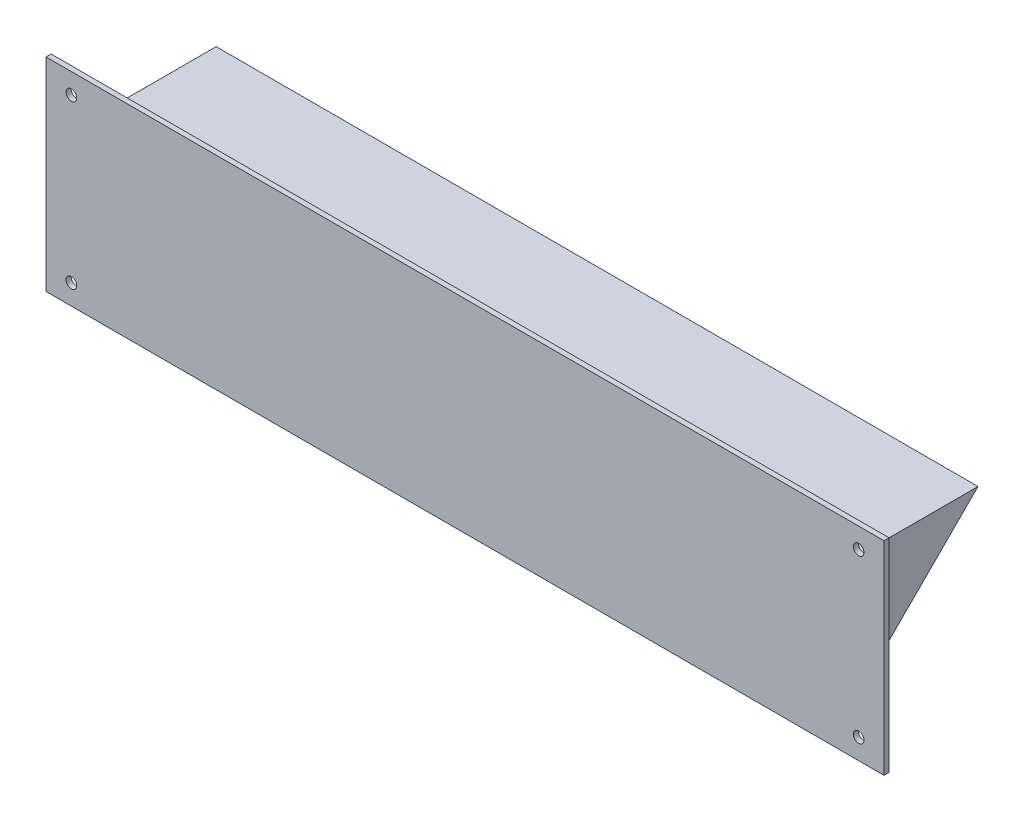
SolidWorks part; units mm, degrees
material "1.4511 (X3CrNb17)"
ref_plane "前视基准面" through (0, 0, 0) normal (0, 0, 1) x (1, 0, 0)
ref_plane "上视基准面" through (0, 0, 0) normal (0, 1, 0) x (1, 0, 0)
ref_plane "右视基准面" through (0, 0, 0) normal (1, 0, 0) x (0, 0, -1)
sketch "草图1" plane through (0, 0, 0) normal (0, 0, 1) x (1, 0, 0)
  line L1 (-165, 40) -> (165, 40)
  line L2 (-165, 40) -> (-165, -40)
  line L3 (-165, -40) -> (165, -40)
  line L4 (165, 40) -> (165, -40)
  line L5 (-165, 40) -> (165, -40) construction
  line L6 (-165, -40) -> (165, 40) construction
  point P0 (0, 0)
  dimension "D1" = 330
  dimension "D2" = 80
extrude "凸台-拉伸1" add sketch "草图1" along normal blind 2
sketch "草图2" plane through (0, 0, 2) normal (0, 0, 1) x (1, 0, 0)
  line L1 (-155, 32) -> (155, 32) construction
  line L2 (-155, 32) -> (-155, -32) construction
  line L3 (-155, -32) -> (155, -32) construction
  line L4 (155, 32) -> (155, -32) construction
  line L5 (-155, 32) -> (155, -32) construction
  line L6 (-155, -32) -> (155, 32) construction
  point P0 (0, 0)
  dimension "D1" = 310
  dimension "D2" = 64
hole_wizard "M5 螺纹孔1" positions "草图3" profile "草图4" tap size "M5" standard "GB" end condition through all
sketch "草图3" plane through (0, 0, 2) normal (0, 0, 1) x (1, 0, 0)
  point P0 (-155, 32)
  point P3 (-155, -32)
  point P6 (155, 32)
  point P9 (155, -32)
sketch "草图4" plane through (-155, 32, 2) normal (1, 0, 0) x (0, -1, 0)
  line L0 (0, 0) -> (0, 2)
  line L1 (0, 2) -> (2.1, 2)
  line L2 (2.1, 2) -> (2.1, 0)
  line L5 (2.1, 0) -> (0, 0)
  line L11 (0, -6.35) -> (0, 107.95) construction
  dimension "通孔螺纹孔钻头直径" = 4.2
  dimension "通孔螺纹孔钻头深度" = 2
cosmetic thread "孔螺蚊线1"
cosmetic thread "孔螺蚊线2"
cosmetic thread "孔螺蚊线3"
cosmetic thread "孔螺蚊线4"
sketch "草图5" plane through (0, 0, 0) normal (1, 0, 0) x (0, 0, -1)
  line L0 (0, 25) -> (0, -25)
  line L1 (0, -40) -> (0, 40) construction
  line L2 (0, 25) -> (50, 25)
  line L3 (50, 25) -> (0, -25)
  point P6 (0, 0)
  dimension "D1" = 50
  dimension "D2" = 50
extrude "凸台-拉伸2" add sketch "草图5" along normal mid plane 300
ref_plane "基准面1" through (140, 0, 0) normal (1, 0, 0) x (0, 0, -1)
sketch "草图6" plane through (140, 0, 0) normal (1, 0, 0) x (0, 0, -1)
  circle A1 centre (25, 0) radius 21.2132
  point P7 (25, 0)
  dimension "D1" = 42.4264
extrude "切除-拉伸1" cut sketch "草图6" against normal blind 280
